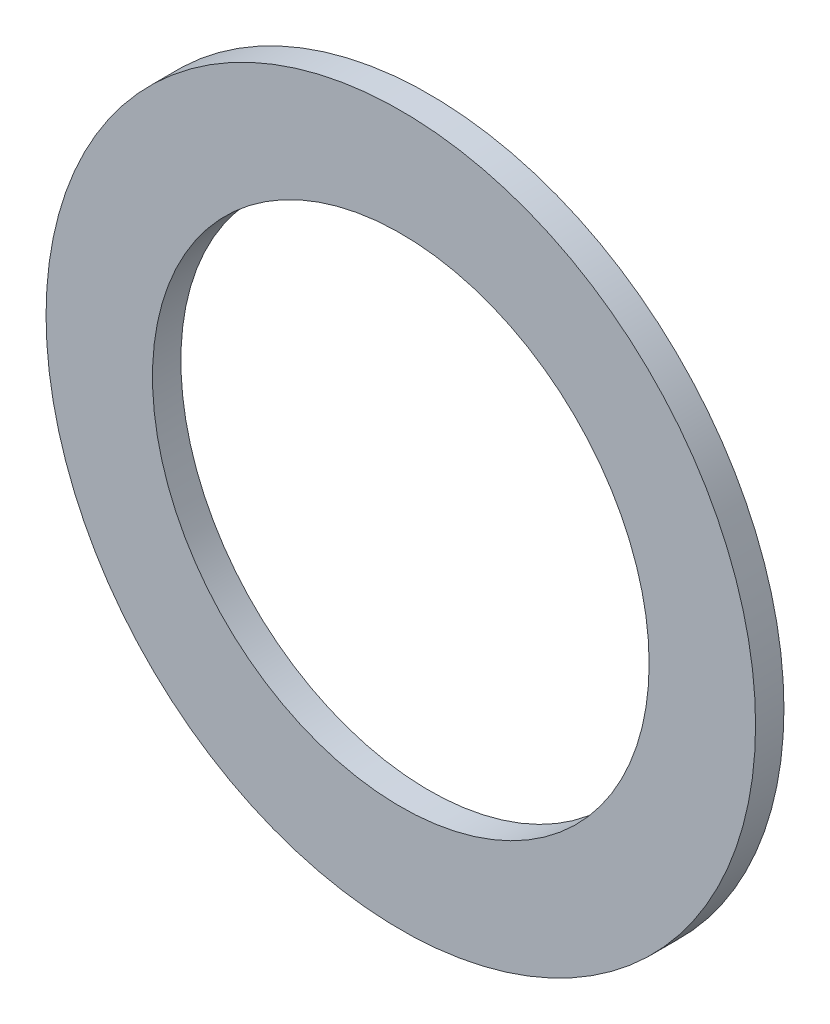
SolidWorks part; units mm, degrees
material "Nylon 101"
ref_plane "Спереди" through (0, 0, 0) normal (0, 0, 1) x (1, 0, 0)
ref_plane "Сверху" through (0, 0, 0) normal (0, 1, 0) x (1, 0, 0)
ref_plane "Справа" through (0, 0, 0) normal (1, 0, 0) x (0, 0, -1)
sketch "Эскиз1" plane through (0, 0, 0) normal (0, 0, 1) x (1, 0, 0)
  circle A37 centre (0, 0) radius 2.5
  circle A39 centre (0, 0) radius 1.75
  dimension "D1" = 5
  dimension "D2" = 3.5
extrude "Бобышка-Вытянуть9" add sketch "Эскиз1" along normal blind 0.2
